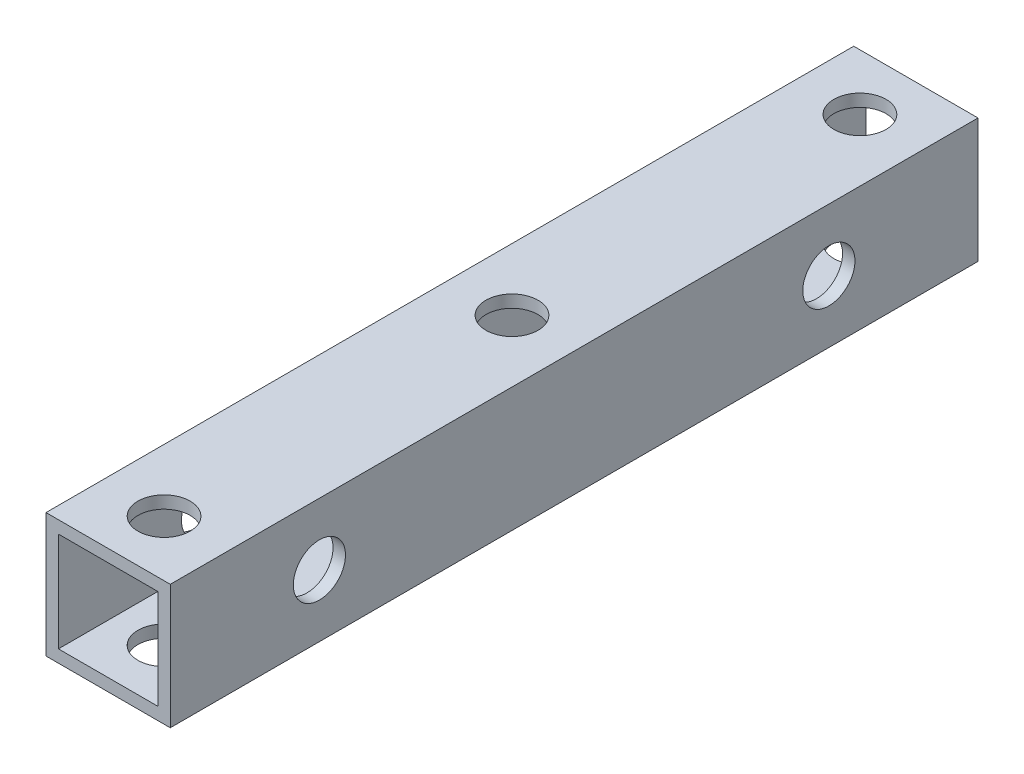
SolidWorks part; units mm, degrees
material "6061 合金"
ref_plane "前视基准面" through (0, 0, 0) normal (0, 0, 1) x (1, 0, 0)
ref_plane "上视基准面" through (0, 0, 0) normal (0, 1, 0) x (1, 0, 0)
ref_plane "右视基准面" through (0, 0, 0) normal (1, 0, 0) x (0, 0, -1)
sketch "草图1" plane through (0, 0, 0) normal (0, 0, 1) x (1, 0, 0)
  line L1 (-4, 4) -> (4, 4)
  line L2 (-4, 4) -> (-4, -4)
  line L3 (-4, -4) -> (4, -4)
  line L4 (4, 4) -> (4, -4)
  line L5 (-4, 4) -> (4, -4) construction
  line L6 (-4, -4) -> (4, 4) construction
  line L7 (-5, 5) -> (5, 5)
  line L8 (-5, 5) -> (-5, -5)
  line L9 (-5, -5) -> (5, -5)
  line L10 (5, 5) -> (5, -5)
  line L11 (-5, 5) -> (5, -5) construction
  line L12 (-5, -5) -> (5, 5) construction
  point P0 (0, 0)
  point P6 (0, 0)
  dimension "D1" = 10
  dimension "D2" = 1
  dimension "D3" = 10
  dimension "D4" = 1
extrude "凸台-拉伸1" add sketch "草图1" along normal blind 65
sketch "草图2" plane through (0, 5, 0) normal (0, 1, 0) x (1, 0, 0)
  line L0 (-5, -32.5) -> (5, -32.5) construction
  line L1 (-5, -65) -> (-5, 0) construction
  line L2 (5, -65) -> (5, 0) construction
  circle A0 centre (0, -4.5) radius 2.1
  circle A1 centre (0, -32.5) radius 2.1
  dimension "D1" = 4.2
  dimension "D3" = 4.2
  dimension "D2" = 56
extrude "切除-拉伸1" cut sketch "草图2" against normal blind 60
ref_plane "基准面1" through (0, 0, 32.5) normal (0, 0, -1) x (-1, 0, 0)
mirror "镜向1" about plane through (0, 0, 32.5) normal (0, 0, -1) of "切除-拉伸1"
sketch "草图3" plane through (-5, 0, 0) normal (-1, 0, 0) x (0, 0, 1)
  line L0 (0, 5) -> (0, -5) construction
  line L1 (0, 0) -> (12, 0) construction
  circle A0 centre (12, 0) radius 2.1
  dimension "D2" = 4.2
  dimension "D1" = 12
extrude "切除-拉伸2" cut sketch "草图3" against normal through all
mirror "镜向2" about plane through (0, 0, 32.5) normal (0, 0, -1) of "切除-拉伸2"
